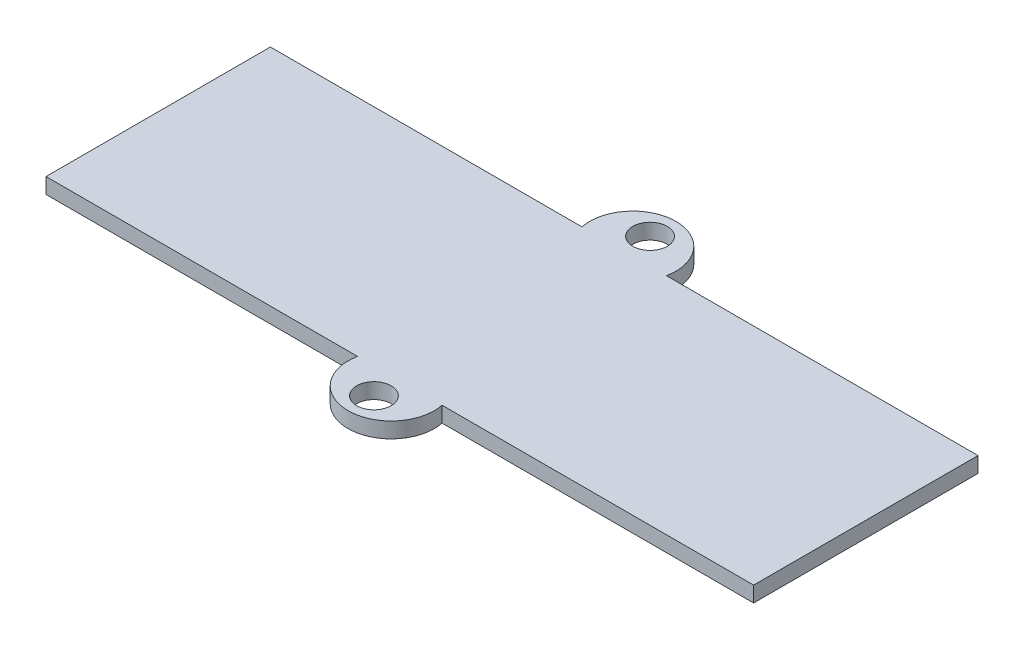
SolidWorks part; units mm, degrees
ref_plane "Front Plane" through (0, 0, 0) normal (0, 0, 1) x (1, 0, 0)
ref_plane "Top Plane" through (0, 0, 0) normal (0, 1, 0) x (1, 0, 0)
ref_plane "Right Plane" through (0, 0, 0) normal (1, 0, 0) x (0, 0, -1)
sketch "Sketch1" plane through (0, 0, 0) normal (0, 1, 0) x (1, 0, 0)
  line L12 (118.1838, 2.0097) -> (82.0828, 2.0097)
  line L13 (82.0828, 2.0097) -> (82.0828, -23.9903)
  line L14 (82.0828, -23.9903) -> (118.1838, -23.9903)
  line L15 (127.9818, -23.9903) -> (164.0828, -23.9903)
  line L16 (164.0828, -23.9903) -> (164.0828, 2.0097)
  line L17 (164.0828, 2.0097) -> (127.9818, 2.0097)
  circle A4 centre (123.0828, 5.0097) radius 2 construction
  circle A5 centre (123.0828, -26.9903) radius 2 construction
  circle A6 centre (123.0828, 5.0097) radius 2
  circle A7 centre (123.0828, -26.9903) radius 2
  arc A8 (118.1838, -23.9903) -> (127.9818, -23.9903) centre (123.0828, -24.9903) ccw
  arc A9 (127.9818, 2.0097) -> (118.1838, 2.0097) centre (123.0828, 3.0097) ccw
extrude "Boss-Extrude1" add sketch "Sketch1" along normal blind 1.8
